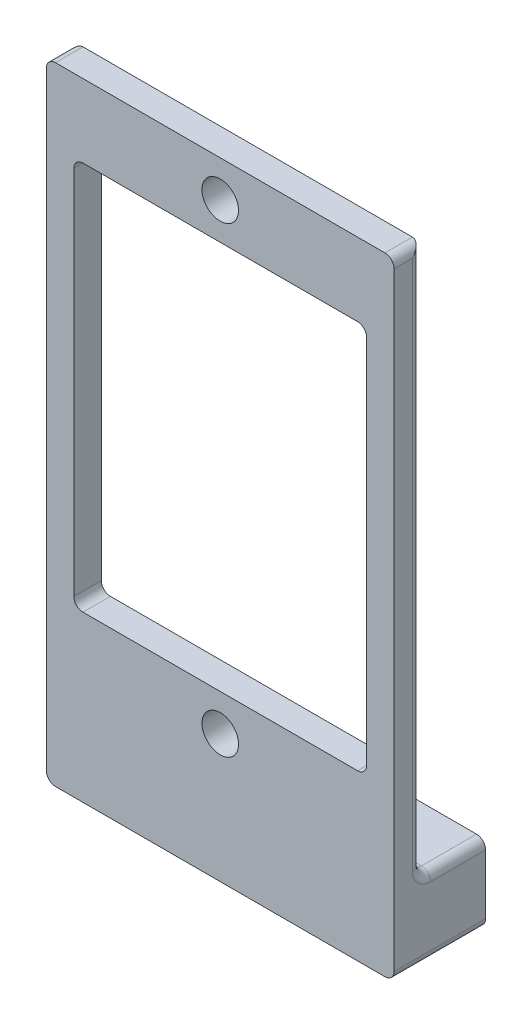
SolidWorks part; units mm, degrees
ref_plane "前视基准面" through (0, 0, 0) normal (0, 0, 1) x (1, 0, 0)
ref_plane "上视基准面" through (0, 0, 0) normal (0, 1, 0) x (1, 0, 0)
ref_plane "右视基准面" through (0, 0, 0) normal (1, 0, 0) x (0, 0, -1)
other "Configuration Table"
sketch "草图1" plane through (0, 0, 0) normal (0, 0, 1) x (1, 0, 0)
  line L0 (0, 21.25) -> (0, -21.25) construction
  line L2 (-12, -21.25) -> (-12, 21.25)
  line L5 (-12, 21.25) -> (20, 21.25)
  line L6 (-12, -21.25) -> (20, -21.25)
  line L7 (0, 21.25) -> (0, 29.25) construction
  line L8 (0, 29.25) -> (23, 29.25)
  line L10 (0, 29.25) -> (-15, 29.25)
  line L11 (-15, 29.25) -> (-15, -39.25)
  line L12 (-15, -39.25) -> (23, -39.25)
  line L13 (0, 25.25) -> (4, 25.25) construction
  line L14 (0, -21.25) -> (0, -25.25) construction
  line L15 (0, -25.25) -> (4, -25.25) construction
  line L16 (23, 29.25) -> (23, -39.25)
  line L17 (20, 21.25) -> (20, -21.25)
  circle A0 centre (4, 25.25) radius 2
  circle A1 centre (4, -25.25) radius 2
  point P0 (0, 0)
extrude "凸台-拉伸1" add sketch "草图1" along normal blind 3
sketch "草图2" plane through (0, 0, 0) normal (0, 0, -1) x (-1, 0, 0)
  line L0 (15, 29.25) -> (15, -39.25) construction
  line L1 (-23, -39.25) -> (15, -39.25)
  line L2 (-23, -39.25) -> (-23, -30.75)
  line L3 (-23, -30.75) -> (15, -30.75)
  line L4 (15, -39.25) -> (15, -30.75)
extrude "凸台-拉伸2" add sketch "草图2" along normal blind 7
fillet "圆角1" radius 1 13 edges at (-12, -21.25, 1.5) (-15, -39.25, -2) (23, -39.25, -2) (23, 29.25, 1.5) (-15, 29.25, 1.5) (-15, -30.75, -3.5) (4, -30.75, 0) (-15, -0.75, 0) (23, -0.75, 0) (23, -30.75, -3.5) (20, -21.25, 1.5) (20, 21.25, 1.5) (-12, 21.25, 1.5)
